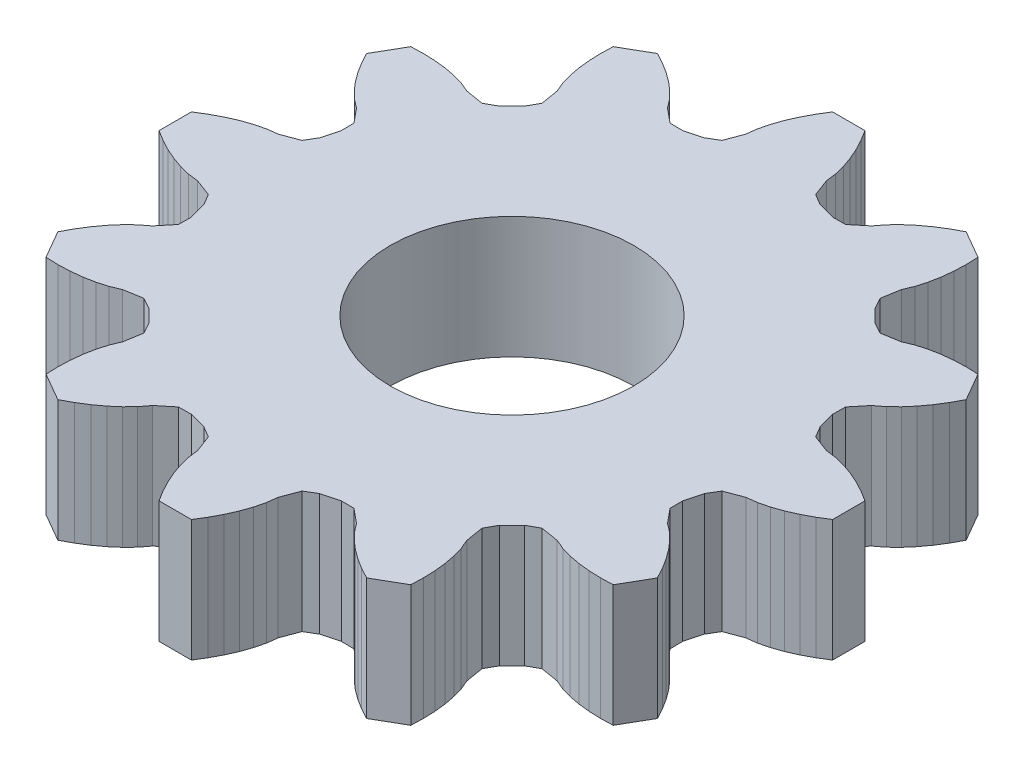
SolidWorks part; units mm, degrees
ref_plane "Спереди" through (0, 0, 0) normal (0, 0, 1) x (1, 0, 0)
ref_plane "Сверху" through (0, 0, 0) normal (0, 1, 0) x (1, 0, 0)
ref_plane "Справа" through (0, 0, 0) normal (1, 0, 0) x (0, 0, -1)
sketch "Эскиз1" plane through (0, 0, 0) normal (0, 1, 0) x (1, 0, 0)
  line L0 (8.2222, 1.8998) -> (8.4363, 1.5395)
  line L1 (8.4363, 1.5395) -> (9.0063, 1.3261)
  line L2 (9.0063, 1.3261) -> (9.3448, 1.2831)
  line L3 (9.3448, 1.2831) -> (9.6877, 1.1978)
  line L4 (9.6877, 1.1978) -> (10.0329, 1.0772)
  line L5 (10.0329, 1.0772) -> (10.3784, 0.9248)
  line L6 (10.3784, 0.9248) -> (10.7229, 0.7422)
  line L7 (10.7229, 0.7422) -> (11.0649, 0.5309)
  line L8 (11.0649, 0.5309) -> (11.0649, -0.5309)
  line L9 (11.0649, -0.5309) -> (10.7229, -0.7422)
  line L10 (10.7229, -0.7422) -> (10.3784, -0.9248)
  line L11 (10.3784, -0.9248) -> (10.0329, -1.0772)
  line L12 (10.0329, -1.0772) -> (9.6877, -1.1978)
  line L13 (9.6877, -1.1978) -> (9.3448, -1.2831)
  line L14 (9.3448, -1.2831) -> (9.0063, -1.3261)
  line L15 (9.0063, -1.3261) -> (8.4363, -1.5395)
  line L16 (8.4363, -1.5395) -> (8.2222, -1.8998)
  line L17 (8.2222, -1.8998) -> (8.0705, -2.4658)
  line L18 (8.0705, -2.4658) -> (8.0758, -2.8849)
  line L19 (8.0758, -2.8849) -> (8.4628, -3.3548)
  line L20 (8.4628, -3.3548) -> (8.7344, -3.5612)
  line L21 (8.7344, -3.5612) -> (8.9887, -3.8066)
  line L22 (8.9887, -3.8066) -> (9.2273, -4.0835)
  line L23 (9.2273, -4.0835) -> (9.4504, -4.3884)
  line L24 (9.4504, -4.3884) -> (9.6574, -4.7187)
  line L25 (9.6574, -4.7187) -> (9.8479, -5.0726)
  line L26 (9.8479, -5.0726) -> (9.317, -5.9922)
  line L27 (9.317, -5.9922) -> (8.9152, -6.0043)
  line L28 (8.9152, -6.0043) -> (8.5256, -5.9901)
  line L29 (8.5256, -5.9901) -> (8.1501, -5.9493)
  line L30 (8.1501, -5.9493) -> (7.7909, -5.8812)
  line L31 (7.7909, -5.8812) -> (7.4513, -5.7836)
  line L32 (7.4513, -5.7836) -> (7.1367, -5.6516)
  line L33 (7.1367, -5.6516) -> (6.5363, -5.5514)
  line L34 (6.5363, -5.5514) -> (6.1707, -5.7563)
  line L35 (6.1707, -5.7563) -> (5.7563, -6.1707)
  line L36 (5.7563, -6.1707) -> (5.5514, -6.5363)
  line L37 (5.5514, -6.5363) -> (5.6516, -7.1367)
  line L38 (5.6516, -7.1367) -> (5.7836, -7.4513)
  line L39 (5.7836, -7.4513) -> (5.8812, -7.7909)
  line L40 (5.8812, -7.7909) -> (5.9493, -8.1501)
  line L41 (5.9493, -8.1501) -> (5.9901, -8.5256)
  line L42 (5.9901, -8.5256) -> (6.0043, -8.9152)
  line L43 (6.0043, -8.9152) -> (5.9922, -9.317)
  line L44 (5.9922, -9.317) -> (5.0726, -9.8479)
  line L45 (5.0726, -9.8479) -> (4.7187, -9.6574)
  line L46 (4.7187, -9.6574) -> (4.3884, -9.4504)
  line L47 (4.3884, -9.4504) -> (4.0835, -9.2273)
  line L48 (4.0835, -9.2273) -> (3.8066, -8.9887)
  line L49 (3.8066, -8.9887) -> (3.5612, -8.7344)
  line L50 (3.5612, -8.7344) -> (3.3548, -8.4628)
  line L51 (3.3548, -8.4628) -> (2.8849, -8.0758)
  line L52 (2.8849, -8.0758) -> (2.4658, -8.0705)
  line L53 (2.4658, -8.0705) -> (1.8998, -8.2222)
  line L54 (1.8998, -8.2222) -> (1.5395, -8.4363)
  line L55 (1.5395, -8.4363) -> (1.3261, -9.0063)
  line L56 (1.3261, -9.0063) -> (1.2831, -9.3448)
  line L57 (1.2831, -9.3448) -> (1.1978, -9.6877)
  line L58 (1.1978, -9.6877) -> (1.0772, -10.0329)
  line L59 (1.0772, -10.0329) -> (0.9248, -10.3784)
  line L60 (0.9248, -10.3784) -> (0.7422, -10.7229)
  line L61 (0.7422, -10.7229) -> (0.5309, -11.0649)
  line L62 (0.5309, -11.0649) -> (-0.5309, -11.0649)
  line L63 (-0.5309, -11.0649) -> (-0.7422, -10.7229)
  line L64 (-0.7422, -10.7229) -> (-0.9248, -10.3784)
  line L65 (-0.9248, -10.3784) -> (-1.0772, -10.0329)
  line L66 (-1.0772, -10.0329) -> (-1.1978, -9.6877)
  line L67 (-1.1978, -9.6877) -> (-1.2831, -9.3448)
  line L68 (-1.2831, -9.3448) -> (-1.3261, -9.0063)
  line L69 (-1.3261, -9.0063) -> (-1.5395, -8.4363)
  line L70 (-1.5395, -8.4363) -> (-1.8998, -8.2222)
  line L71 (-1.8998, -8.2222) -> (-2.4658, -8.0705)
  line L72 (-2.4658, -8.0705) -> (-2.8849, -8.0758)
  line L73 (-2.8849, -8.0758) -> (-3.3548, -8.4628)
  line L74 (-3.3548, -8.4628) -> (-3.5612, -8.7344)
  line L75 (-3.5612, -8.7344) -> (-3.8066, -8.9887)
  line L76 (-3.8066, -8.9887) -> (-4.0835, -9.2273)
  line L77 (-4.0835, -9.2273) -> (-4.3884, -9.4504)
  line L78 (-4.3884, -9.4504) -> (-4.7187, -9.6574)
  line L79 (-4.7187, -9.6574) -> (-5.0726, -9.8479)
  line L80 (-5.0726, -9.8479) -> (-5.9922, -9.317)
  line L81 (-5.9922, -9.317) -> (-6.0043, -8.9152)
  line L82 (-6.0043, -8.9152) -> (-5.9901, -8.5256)
  line L83 (-5.9901, -8.5256) -> (-5.9493, -8.1501)
  line L84 (-5.9493, -8.1501) -> (-5.8812, -7.7909)
  line L85 (-5.8812, -7.7909) -> (-5.7836, -7.4513)
  line L86 (-5.7836, -7.4513) -> (-5.6516, -7.1367)
  line L87 (-5.6516, -7.1367) -> (-5.5514, -6.5363)
  line L88 (-5.5514, -6.5363) -> (-5.7563, -6.1707)
  line L89 (-5.7563, -6.1707) -> (-6.1707, -5.7563)
  line L90 (-6.1707, -5.7563) -> (-6.5363, -5.5514)
  line L91 (-6.5363, -5.5514) -> (-7.1367, -5.6516)
  line L92 (-7.1367, -5.6516) -> (-7.4513, -5.7836)
  line L93 (-7.4513, -5.7836) -> (-7.7909, -5.8812)
  line L94 (-7.7909, -5.8812) -> (-8.1501, -5.9493)
  line L95 (-8.1501, -5.9493) -> (-8.5256, -5.9901)
  line L96 (-8.5256, -5.9901) -> (-8.9152, -6.0043)
  line L97 (-8.9152, -6.0043) -> (-9.317, -5.9922)
  line L98 (-9.317, -5.9922) -> (-9.8479, -5.0726)
  line L99 (-9.8479, -5.0726) -> (-9.6574, -4.7187)
  line L100 (-9.6574, -4.7187) -> (-9.4504, -4.3884)
  line L101 (-9.4504, -4.3884) -> (-9.2273, -4.0835)
  line L102 (-9.2273, -4.0835) -> (-8.9887, -3.8066)
  line L103 (-8.9887, -3.8066) -> (-8.7344, -3.5612)
  line L104 (-8.7344, -3.5612) -> (-8.4628, -3.3548)
  line L105 (-8.4628, -3.3548) -> (-8.0758, -2.8849)
  line L106 (-8.0758, -2.8849) -> (-8.0705, -2.4658)
  line L107 (-8.0705, -2.4658) -> (-8.2222, -1.8998)
  line L108 (-8.2222, -1.8998) -> (-8.4363, -1.5395)
  line L109 (-8.4363, -1.5395) -> (-9.0063, -1.3261)
  line L110 (-9.0063, -1.3261) -> (-9.3448, -1.2831)
  line L111 (-9.3448, -1.2831) -> (-9.6877, -1.1978)
  line L112 (-9.6877, -1.1978) -> (-10.0329, -1.0772)
  line L113 (-10.0329, -1.0772) -> (-10.3784, -0.9248)
  line L114 (-10.3784, -0.9248) -> (-10.7229, -0.7422)
  line L115 (-10.7229, -0.7422) -> (-11.0649, -0.5309)
  line L116 (-11.0649, -0.5309) -> (-11.0649, 0.5309)
  line L117 (-11.0649, 0.5309) -> (-10.7229, 0.7422)
  line L118 (-10.7229, 0.7422) -> (-10.3784, 0.9248)
  line L119 (-10.3784, 0.9248) -> (-10.0329, 1.0772)
  line L120 (-10.0329, 1.0772) -> (-9.6877, 1.1978)
  line L121 (-9.6877, 1.1978) -> (-9.3448, 1.2831)
  line L122 (-9.3448, 1.2831) -> (-9.0063, 1.3261)
  line L123 (-9.0063, 1.3261) -> (-8.4363, 1.5395)
  line L124 (-8.4363, 1.5395) -> (-8.2222, 1.8998)
  line L125 (-8.2222, 1.8998) -> (-8.0705, 2.4658)
  line L126 (-8.0705, 2.4658) -> (-8.0758, 2.8849)
  line L127 (-8.0758, 2.8849) -> (-8.4628, 3.3548)
  line L128 (-8.4628, 3.3548) -> (-8.7344, 3.5612)
  line L129 (-8.7344, 3.5612) -> (-8.9887, 3.8066)
  line L130 (-8.9887, 3.8066) -> (-9.2273, 4.0835)
  line L131 (-9.2273, 4.0835) -> (-9.4504, 4.3884)
  line L132 (-9.4504, 4.3884) -> (-9.6574, 4.7187)
  line L133 (-9.6574, 4.7187) -> (-9.8479, 5.0726)
  line L134 (-9.8479, 5.0726) -> (-9.317, 5.9922)
  line L135 (-9.317, 5.9922) -> (-8.9152, 6.0043)
  line L136 (-8.9152, 6.0043) -> (-8.5256, 5.9901)
  line L137 (-8.5256, 5.9901) -> (-8.1501, 5.9493)
  line L138 (-8.1501, 5.9493) -> (-7.7909, 5.8812)
  line L139 (-7.7909, 5.8812) -> (-7.4513, 5.7836)
  line L140 (-7.4513, 5.7836) -> (-7.1367, 5.6516)
  line L141 (-7.1367, 5.6516) -> (-6.5363, 5.5514)
  line L142 (-6.5363, 5.5514) -> (-6.1707, 5.7563)
  line L143 (-6.1707, 5.7563) -> (-5.7563, 6.1707)
  line L144 (-5.7563, 6.1707) -> (-5.5514, 6.5363)
  line L145 (-5.5514, 6.5363) -> (-5.6516, 7.1367)
  line L146 (-5.6516, 7.1367) -> (-5.7836, 7.4513)
  line L147 (-5.7836, 7.4513) -> (-5.8812, 7.7909)
  line L148 (-5.8812, 7.7909) -> (-5.9493, 8.1501)
  line L149 (-5.9493, 8.1501) -> (-5.9901, 8.5256)
  line L150 (-5.9901, 8.5256) -> (-6.0043, 8.9152)
  line L151 (-6.0043, 8.9152) -> (-5.9922, 9.317)
  line L152 (-5.9922, 9.317) -> (-5.0726, 9.8479)
  line L153 (-5.0726, 9.8479) -> (-4.7187, 9.6574)
  line L154 (-4.7187, 9.6574) -> (-4.3884, 9.4504)
  line L155 (-4.3884, 9.4504) -> (-4.0835, 9.2273)
  line L156 (-4.0835, 9.2273) -> (-3.8066, 8.9887)
  line L157 (-3.8066, 8.9887) -> (-3.5612, 8.7344)
  line L158 (-3.5612, 8.7344) -> (-3.3548, 8.4628)
  line L159 (-3.3548, 8.4628) -> (-2.8849, 8.0758)
  line L160 (-2.8849, 8.0758) -> (-2.4658, 8.0705)
  line L161 (-2.4658, 8.0705) -> (-1.8998, 8.2222)
  line L162 (-1.8998, 8.2222) -> (-1.5395, 8.4363)
  line L163 (-1.5395, 8.4363) -> (-1.3261, 9.0063)
  line L164 (-1.3261, 9.0063) -> (-1.2831, 9.3448)
  line L165 (-1.2831, 9.3448) -> (-1.1978, 9.6877)
  line L166 (-1.1978, 9.6877) -> (-1.0772, 10.0329)
  line L167 (-1.0772, 10.0329) -> (-0.9248, 10.3784)
  line L168 (-0.9248, 10.3784) -> (-0.7422, 10.7229)
  line L169 (-0.7422, 10.7229) -> (-0.5309, 11.0649)
  line L170 (-0.5309, 11.0649) -> (0.5309, 11.0649)
  line L171 (0.5309, 11.0649) -> (0.7422, 10.7229)
  line L172 (0.7422, 10.7229) -> (0.9248, 10.3784)
  line L173 (0.9248, 10.3784) -> (1.0772, 10.0329)
  line L174 (1.0772, 10.0329) -> (1.1978, 9.6877)
  line L175 (1.1978, 9.6877) -> (1.2831, 9.3448)
  line L176 (1.2831, 9.3448) -> (1.3261, 9.0063)
  line L177 (1.3261, 9.0063) -> (1.5395, 8.4363)
  line L178 (1.5395, 8.4363) -> (1.8998, 8.2222)
  line L179 (1.8998, 8.2222) -> (2.4658, 8.0705)
  line L180 (2.4658, 8.0705) -> (2.8849, 8.0758)
  line L181 (2.8849, 8.0758) -> (3.3548, 8.4628)
  line L182 (3.3548, 8.4628) -> (3.5612, 8.7344)
  line L183 (3.5612, 8.7344) -> (3.8066, 8.9887)
  line L184 (3.8066, 8.9887) -> (4.0835, 9.2273)
  line L185 (4.0835, 9.2273) -> (4.3884, 9.4504)
  line L186 (4.3884, 9.4504) -> (4.7187, 9.6574)
  line L187 (4.7187, 9.6574) -> (5.0726, 9.8479)
  line L188 (5.0726, 9.8479) -> (5.9922, 9.317)
  line L189 (5.9922, 9.317) -> (6.0043, 8.9152)
  line L190 (6.0043, 8.9152) -> (5.9901, 8.5256)
  line L191 (5.9901, 8.5256) -> (5.9493, 8.1501)
  line L192 (5.9493, 8.1501) -> (5.8812, 7.7909)
  line L193 (5.8812, 7.7909) -> (5.7836, 7.4513)
  line L194 (5.7836, 7.4513) -> (5.6516, 7.1367)
  line L195 (5.6516, 7.1367) -> (5.5514, 6.5363)
  line L196 (5.5514, 6.5363) -> (5.7563, 6.1707)
  line L197 (5.7563, 6.1707) -> (6.1707, 5.7563)
  line L198 (6.1707, 5.7563) -> (6.5363, 5.5514)
  line L199 (6.5363, 5.5514) -> (7.1367, 5.6516)
  line L200 (7.1367, 5.6516) -> (7.4513, 5.7836)
  line L201 (7.4513, 5.7836) -> (7.7909, 5.8812)
  line L202 (7.7909, 5.8812) -> (8.1501, 5.9493)
  line L203 (8.1501, 5.9493) -> (8.5256, 5.9901)
  line L204 (8.5256, 5.9901) -> (8.9152, 6.0043)
  line L205 (8.9152, 6.0043) -> (9.317, 5.9922)
  line L206 (9.317, 5.9922) -> (9.8479, 5.0726)
  line L207 (9.8479, 5.0726) -> (9.6574, 4.7187)
  line L208 (9.6574, 4.7187) -> (9.4504, 4.3884)
  line L209 (9.4504, 4.3884) -> (9.2273, 4.0835)
  line L210 (9.2273, 4.0835) -> (8.9887, 3.8066)
  line L211 (8.9887, 3.8066) -> (8.7344, 3.5612)
  line L212 (8.7344, 3.5612) -> (8.4628, 3.3548)
  line L213 (8.4628, 3.3548) -> (8.0758, 2.8849)
  line L214 (8.0758, 2.8849) -> (8.0705, 2.4658)
  line L215 (8.0705, 2.4658) -> (8.2222, 1.8998)
  line L216 (0, -1) -> (0, 1) construction
  line L217 (-1, 0) -> (1, 0) construction
  circle A0 centre (0, 0) radius 4
  dimension "D1" = 8
extrude "Бобышка-Вытянуть1" add sketch "Эскиз1" along normal blind 4
